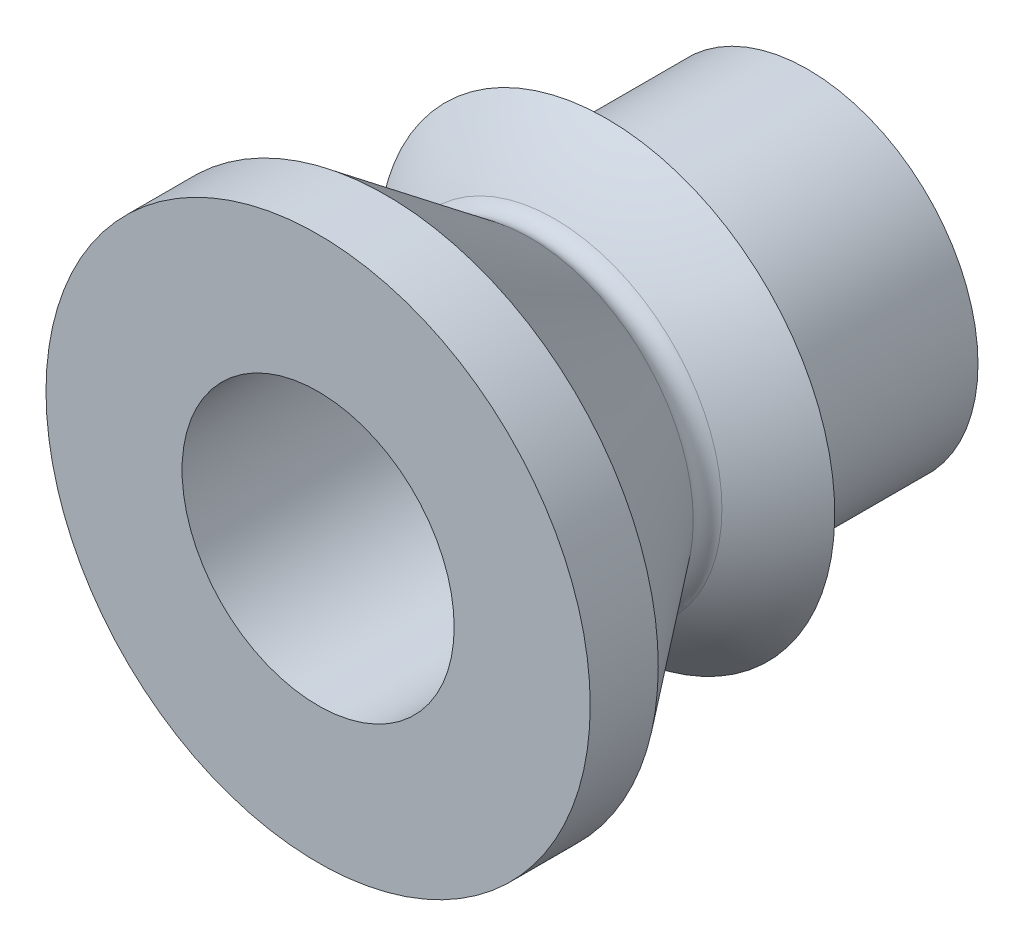
SolidWorks part; units mm, degrees
material "AISI 304"
ref_plane "Front Plane" through (0, 0, 0) normal (0, 0, 1) x (1, 0, 0)
ref_plane "Top Plane" through (0, 0, 0) normal (0, 1, 0) x (1, 0, 0)
ref_plane "Right Plane" through (0, 0, 0) normal (1, 0, 0) x (0, 0, -1)
sketch "Sketch1" plane through (0, 0, 0) normal (1, 0, 0) x (0, 0, -1)
  line L0 (-29.3064, 0) -> (29.3064, 0) construction
  line L3 (0, 0) -> (0, 40.3478) construction
  line L7 (-47.2757, 0) -> (47.2757, 0) construction
  line L10 (-0.127, 6.35) -> (-0.127, 7.9375)
  line L11 (-0.127, 7.9375) -> (-9.525, 7.9375)
  line L12 (-9.525, 7.9375) -> (-9.525, 10.6493)
  line L13 (-0.127, 6.35) -> (-22.987, 6.35)
  line L14 (-22.987, 6.35) -> (-22.987, 12.7)
  line L15 (-22.987, 12.7) -> (-19.812, 12.7)
  line L16 (-19.812, 12.7) -> (-13.1019, 7.62)
  arc A1 (-9.525, 10.6493) -> (-11.9584, 7.8185) centre (0, 0) ccw
  arc A2 (-11.9584, 7.8185) -> (-13.1019, 7.62) centre (-12.6228, 8.2528) cw
  dimension "D12" = 14.2875
  dimension "D9" = 0.7937
  dimension "D15" = 15.24
  dimension "D6" = 25.4
  dimension "D7" = 12.7
  dimension "D8" = 15.875
  dimension "D10" = 13.462
  dimension "D11" = 22.86
  dimension "D13" = 9.525
  dimension "D14" = 3.175
revolve "Revolve1" add sketch "Sketch1" angle 360 about L7
